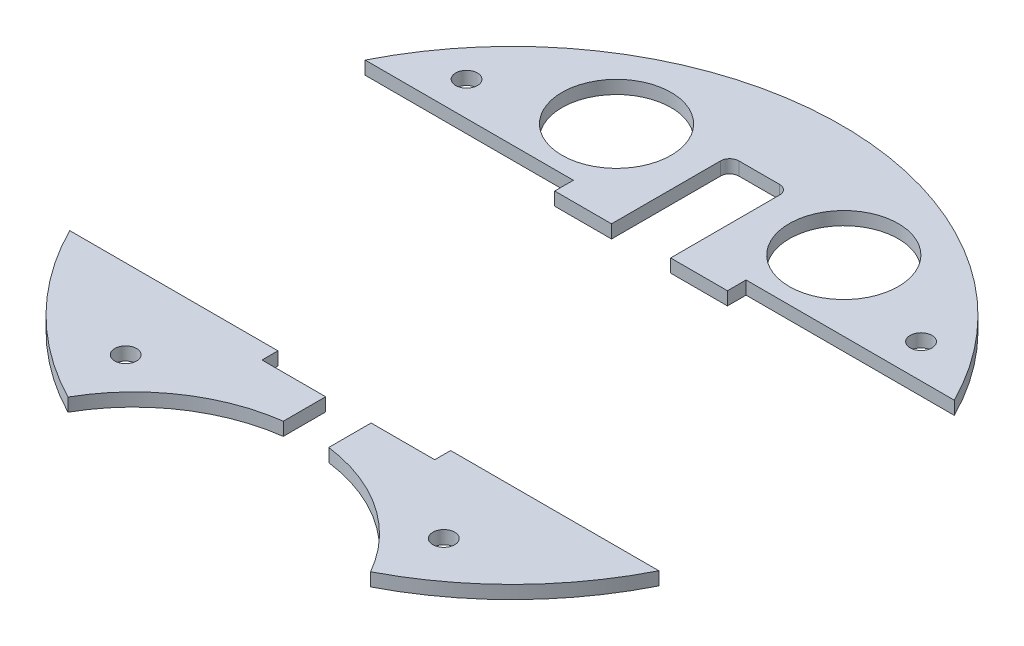
SolidWorks part; units mm, degrees
material "Acrylic (Medium-high impact)"
ref_plane "Front Plane" through (0, 0, 0) normal (0, 0, 1) x (1, 0, 0)
ref_plane "Top Plane" through (0, 0, 0) normal (0, 1, 0) x (1, 0, 0)
ref_plane "Right Plane" through (0, 0, 0) normal (1, 0, 0) x (0, 0, -1)
sketch "Sketch1" plane through (0, 0, 0) normal (0, 1, 0) x (1, 0, 0)
  line L0 (0, -83.2398) -> (-33.2911, -64.4046) construction
  line L1 (0, -83.2398) -> (0, 0) construction
  arc A0 (33.2911, -64.4046) -> (-33.2911, -64.4046) centre (0, 0) ccw
  arc A1 (33.2911, -64.4046) -> (-33.2911, -64.4046) centre (0, -83.2398) ccw
  dimension "D1" = 145
  dimension "D2" = 76.5
  dimension "D3" = 60.5
extrude "Boss-Extrude1" add sketch "Sketch1" along normal blind 2.9
sketch "solenoid placement" plane through (0, 2.9, 0) normal (0, 1, 0) x (1, 0, 0)
  line L4 (-19, -36) -> (19, -36)
  line L5 (-19, 28.4) -> (-19, -36)
  line L6 (19, 28.4) -> (-19, 28.4)
  line L7 (19, -36) -> (19, 28.4)
  line L8 (-19, -36) -> (19, -36)
  line L9 (-19, 28.4) -> (-19, -36)
  line L10 (19, 28.4) -> (-19, 28.4)
  line L11 (19, -36) -> (19, 28.4)
  dimension "D1" = 0
extrude "Cut-Extrude1" cut sketch "solenoid placement" against normal through all
sketch "Sketch4" plane through (0, 2.9, 0) normal (0, 1, 0) x (1, 0, 0)
  line L6 (-6.5, 28.1) -> (6.5, 28.1)
  line L7 (6.5, 28.1) -> (6.5, 52.4)
  line L8 (4.5, 54.4) -> (-4.5, 54.4)
  line L9 (-6.5, 52.4) -> (-6.5, 28.1)
  line L10 (-6.5, 28.1) -> (6.5, 28.1)
  line L11 (6.5, 28.1) -> (6.5, 52.4)
  line L12 (4.5, 54.4) -> (-4.5, 54.4)
  line L13 (-6.5, 52.4) -> (-6.5, 28.1)
  arc A4 (6.5, 52.4) -> (4.5, 54.4) centre (4.5, 52.4) ccw
  arc A5 (6.5, 52.4) -> (4.5, 54.4) centre (4.5, 52.4) ccw
  arc A6 (-4.5, 54.4) -> (-6.5, 52.4) centre (-4.5, 52.4) ccw
  arc A7 (-4.5, 54.4) -> (-6.5, 52.4) centre (-4.5, 52.4) ccw
  dimension "D1" = 0
extrude "Cut-Extrude4" cut sketch "Sketch4" against normal through all
sketch "Sketch5" plane through (0, 2.9, 0) normal (0, 1, 0) x (1, 0, 0)
  circle A1 centre (-25, 48) radius 12
  circle A2 centre (-25, 48) radius 12
  circle A3 centre (25, 48) radius 12
  circle A4 centre (25, 48) radius 12
  dimension "D1" = 0
  dimension "D2" = 0
extrude "Cut-Extrude5" cut sketch "Sketch5" against normal through all
sketch "Sketch6" plane through (0, 2.9, 0) normal (0, 1, 0) x (1, 0, 0)
  circle A1 centre (35, -50) radius 2.4
  circle A2 centre (35, -50) radius 2.4
  circle A3 centre (-35, -50) radius 2.4
  circle A4 centre (-35, -50) radius 2.4
  circle A5 centre (-50, 40) radius 2.4
  circle A6 centre (-50, 40) radius 2.4
  circle A7 centre (50, 40) radius 2.4
  circle A8 centre (50, 40) radius 2.4
  dimension "D1" = 0
  dimension "D2" = 0
  dimension "D3" = 0
  dimension "D4" = 0
extrude "Cut-Extrude6" cut sketch "Sketch6" against normal through all
sketch "Sketch3" plane through (0, 2.9, 0) normal (0, 1, 0) x (1, 0, 0)
  line L0 (-19, 28.4) -> (19, 28.4)
  line L1 (-72.5, -32.5) -> (72.5, -32.5)
  line L2 (-72.5, -32.5) -> (-72.5, 32.5)
  line L3 (-72.5, 32.5) -> (-19, 32.5)
  line L4 (72.5, -32.5) -> (72.5, 32.5)
  line L5 (-72.5, -32.5) -> (72.5, 32.5) construction
  line L6 (-72.5, 32.5) -> (72.5, -32.5) construction
  line L7 (19, 28.4) -> (19, 32.5)
  line L8 (-19, 28.4) -> (-19, 32.5)
  line L9 (19, 32.5) -> (72.5, 32.5)
  arc A0 (33.2911, -64.4046) -> (-33.2911, -64.4046) centre (0, 0) ccw construction
  point P0 (0, 0)
  dimension "D1" = 65
extrude "Cut-Extrude3" cut sketch "Sketch3" against normal through all
sketch "Sketch8" plane through (0, 2.9, 0) normal (0, 1, 0) x (1, 0, 0)
  line L4 (5, 0) -> (-5, 0)
  line L5 (5, -62.8025) -> (5, 0)
  line L6 (-5, -62.8025) -> (5, -62.8025)
  line L7 (-5, 0) -> (-5, -62.8025)
  line L8 (5, 0) -> (-5, 0)
  line L9 (5, -62.8025) -> (5, 0)
  line L10 (-5, -62.8025) -> (5, -62.8025)
  line L11 (-5, 0) -> (-5, -62.8025)
  dimension "D1" = 0
extrude "Cut-Extrude9" cut sketch "Sketch8" against normal through all and the other way through all
equation "\"smallPulleyTeeth\"= 15"
equation "\"largePulleyTeeth\"= 30"
equation "\"eighthThick\"= 2.9mm"
equation "\"sixteenthThick\" = 1.7mm"
equation "\"quarterThick\"=6.0mm"
equation "\"OD\" = 145mm"
equation "\"puckAngle\" = 60.5deg"
equation "\"D1@Sketch1\"=\"OD\""
equation "\"puckDiam\" = 76.5mm"
equation "\"D2@Sketch1\"=\"puckDiam\""
equation "\"D3@Sketch1\"=\"puckAngle\""
equation "\"D1@Boss-Extrude1\"=\"eighthThick\""
equation "\"axlePress\" = 5.9mm"
equation "\"press\" = 0.2mm"
equation "\"wheelClear\" = 0.3mm"
equation "\"10-32clear\" = 4.8mm"
equation "\"6-32clear\" = 3.3mm"
equation "\"8-32clear\" = 4.0mm"
equation "\"wheelHeight\" = 22mm"
equation "\"wheelWell\" = 65mm"
equation "\"D1@Sketch3\"=\"wheelWell\""
